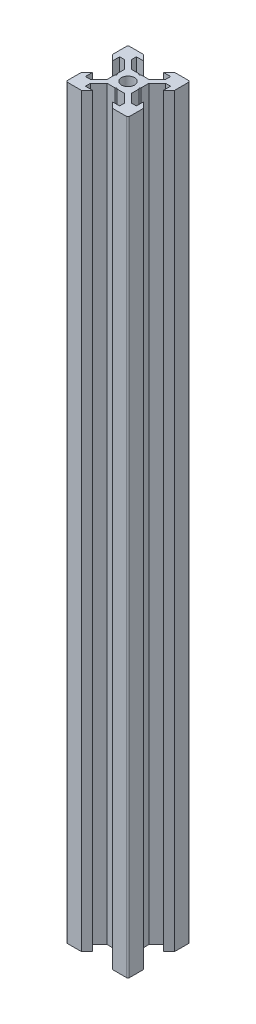
SolidWorks part; units mm, degrees
material "6063-O，挤压棒材(SS)"
ref_plane "前视基准面" through (0, 0, 0) normal (0, 0, 1) x (1, 0, 0)
ref_plane "上视基准面" through (0, 0, 0) normal (0, 1, 0) x (1, 0, 0)
ref_plane "右视基准面" through (0, 0, 0) normal (1, 0, 0) x (0, 0, -1)
other "Configuration Table"
sketch "草图1" plane through (0, 0, 0) normal (0, 1, 0) x (1, 0, 0)
  line L0 (-2.0109, 3.9) -> (2.0109, 3.9)
  line L1 (3.4251, 4.4858) -> (5.5, 6.5607)
  line L2 (5.5, 6.5607) -> (5.5, 8.2)
  line L3 (5.5, 8.2) -> (3.3, 8.2)
  line L4 (3.1, 8.4) -> (3.1, 9.3)
  line L5 (3.8, 10) -> (8.5, 10)
  line L6 (10, 8.5) -> (10, 3.8)
  line L7 (9.3, 3.1) -> (8.4, 3.1)
  line L8 (8.2, 3.3) -> (8.2, 5.5)
  line L9 (8.2, 5.5) -> (6.5607, 5.5)
  line L10 (6.5607, 5.5) -> (4.4858, 3.4251)
  line L11 (3.9, 2.0109) -> (3.9, -2.0109)
  line L12 (4.4858, -3.4251) -> (6.5607, -5.5)
  line L13 (6.5607, -5.5) -> (8.2, -5.5)
  line L14 (8.2, -5.5) -> (8.2, -3.3)
  line L15 (8.4, -3.1) -> (9.3, -3.1)
  line L16 (10, -3.8) -> (10, -8.5)
  line L17 (8.5, -10) -> (3.8, -10)
  line L18 (3.1, -9.3) -> (3.1, -8.4)
  line L19 (3.3, -8.2) -> (5.5, -8.2)
  line L20 (5.5, -8.2) -> (5.5, -6.5607)
  line L21 (5.5, -6.5607) -> (3.4251, -4.4858)
  line L22 (2.0109, -3.9) -> (-2.0109, -3.9)
  line L23 (-3.4251, -4.4858) -> (-5.5, -6.5607)
  line L24 (-5.5, -6.5607) -> (-5.5, -8.2)
  line L25 (-5.5, -8.2) -> (-3.3, -8.2)
  line L26 (-3.1, -8.4) -> (-3.1, -9.3)
  line L27 (-3.8, -10) -> (-8.5, -10)
  line L28 (-10, -8.5) -> (-10, -3.8)
  line L29 (-9.3, -3.1) -> (-8.4, -3.1)
  line L30 (-8.2, -3.3) -> (-8.2, -5.5)
  line L31 (-8.2, -5.5) -> (-6.5607, -5.5)
  line L32 (-6.5607, -5.5) -> (-4.4858, -3.4251)
  line L33 (-3.9, -2.0109) -> (-3.9, 2.0109)
  line L34 (-4.4858, 3.4251) -> (-6.5607, 5.5)
  line L35 (-6.5607, 5.5) -> (-8.2, 5.5)
  line L36 (-8.2, 5.5) -> (-8.2, 3.3)
  line L37 (-8.4, 3.1) -> (-9.3, 3.1)
  line L38 (-10, 3.8) -> (-10, 8.5)
  line L39 (-8.5, 10) -> (-3.8, 10)
  line L40 (-3.1, 9.3) -> (-3.1, 8.4)
  line L41 (-3.3, 8.2) -> (-5.5, 8.2)
  line L42 (-5.5, 8.2) -> (-5.5, 6.5607)
  line L43 (-5.5, 6.5607) -> (-3.4251, 4.4858)
  line L44 (-4.4858, 3.4251) -> (-3.4251, 4.4858) construction
  line L45 (3.4251, 4.4858) -> (4.4858, 3.4251) construction
  line L46 (4.4858, -3.4251) -> (3.4251, -4.4858) construction
  line L47 (-3.4251, -4.4858) -> (-4.4858, -3.4251) construction
  line L48 (3.9555, -3.9555) -> (-3.9555, 3.9555) construction
  line L49 (3.9555, 3.9555) -> (-3.9555, -3.9555) construction
  line L50 (-9.5, 3.3) -> (-9.5, 3.6)
  line L51 (-9.5, 3.6) -> (-9.8, 3.6)
  line L52 (-3.6, 9.8) -> (-3.6, 9.5)
  line L53 (-3.6, 9.5) -> (-3.3, 9.5)
  line L54 (3.3, 9.5) -> (3.6, 9.5)
  line L55 (3.6, 9.5) -> (3.6, 9.8)
  line L56 (9.5, 3.3) -> (9.5, 3.6)
  line L57 (9.5, 3.6) -> (9.8, 3.6)
  line L58 (9.5, -3.3) -> (9.5, -3.6)
  line L59 (9.5, -3.6) -> (9.8, -3.6)
  line L60 (3.3, -9.5) -> (3.6, -9.5)
  line L61 (3.6, -9.5) -> (3.6, -9.8)
  line L62 (-3.6, -9.8) -> (-3.6, -9.5)
  line L63 (-3.6, -9.5) -> (-3.3, -9.5)
  line L64 (-9.5, -3.3) -> (-9.5, -3.6)
  line L65 (-9.5, -3.6) -> (-9.8, -3.6)
  arc A1 (2.0109, 3.9) -> (3.4251, 4.4858) centre (2.0109, 5.9) ccw
  arc A2 (3.3, 8.2) -> (3.1, 8.4) centre (3.3, 8.4) cw
  arc A5 (8.5, 10) -> (10, 8.5) centre (8.5, 8.5) cw
  arc A8 (8.4, 3.1) -> (8.2, 3.3) centre (8.4, 3.3) cw
  arc A9 (4.4858, 3.4251) -> (3.9, 2.0109) centre (5.9, 2.0109) ccw
  arc A10 (3.9, -2.0109) -> (4.4858, -3.4251) centre (5.9, -2.0109) ccw
  arc A11 (8.2, -3.3) -> (8.4, -3.1) centre (8.4, -3.3) cw
  arc A14 (10, -8.5) -> (8.5, -10) centre (8.5, -8.5) cw
  arc A17 (3.1, -8.4) -> (3.3, -8.2) centre (3.3, -8.4) cw
  arc A18 (3.4251, -4.4858) -> (2.0109, -3.9) centre (2.0109, -5.9) ccw
  arc A19 (-2.0109, -3.9) -> (-3.4251, -4.4858) centre (-2.0109, -5.9) ccw
  arc A20 (-3.3, -8.2) -> (-3.1, -8.4) centre (-3.3, -8.4) cw
  arc A23 (-8.5, -10) -> (-10, -8.5) centre (-8.5, -8.5) cw
  arc A26 (-8.4, -3.1) -> (-8.2, -3.3) centre (-8.4, -3.3) cw
  arc A27 (-4.4858, -3.4251) -> (-3.9, -2.0109) centre (-5.9, -2.0109) ccw
  arc A28 (-3.9, 2.0109) -> (-4.4858, 3.4251) centre (-5.9, 2.0109) ccw
  arc A29 (-8.2, 3.3) -> (-8.4, 3.1) centre (-8.4, 3.3) cw
  arc A32 (-10, 8.5) -> (-8.5, 10) centre (-8.5, 8.5) cw
  arc A35 (-3.1, 8.4) -> (-3.3, 8.2) centre (-3.3, 8.4) cw
  arc A36 (-3.4251, 4.4858) -> (-2.0109, 3.9) centre (-2.0109, 5.9) ccw
  arc A37 (-9.3, 3.1) -> (-9.5, 3.3) centre (-9.3, 3.3) cw
  arc A39 (-3.8, 10) -> (-3.6, 9.8) centre (-3.8, 9.8) cw
  arc A40 (-3.3, 9.5) -> (-3.1, 9.3) centre (-3.3, 9.3) cw
  arc A41 (3.1, 9.3) -> (3.3, 9.5) centre (3.3, 9.3) cw
  arc A42 (3.6, 9.8) -> (3.8, 10) centre (3.8, 9.8) cw
  arc A43 (9.3, 3.1) -> (9.5, 3.3) centre (9.3, 3.3) ccw
  arc A44 (9.8, 3.6) -> (10, 3.8) centre (9.8, 3.8) ccw
  arc A45 (9.3, -3.1) -> (9.5, -3.3) centre (9.3, -3.3) cw
  arc A46 (9.8, -3.6) -> (10, -3.8) centre (9.8, -3.8) cw
  arc A47 (3.1, -9.3) -> (3.3, -9.5) centre (3.3, -9.3) ccw
  arc A48 (3.6, -9.8) -> (3.8, -10) centre (3.8, -9.8) ccw
  arc A49 (-3.8, -10) -> (-3.6, -9.8) centre (-3.8, -9.8) ccw
  arc A50 (-3.3, -9.5) -> (-3.1, -9.3) centre (-3.3, -9.3) ccw
  arc A51 (-9.3, -3.1) -> (-9.5, -3.3) centre (-9.3, -3.3) ccw
  arc A53 (-9.8, 3.6) -> (-10, 3.8) centre (-9.8, 3.8) cw
  arc A54 (-9.8, -3.6) -> (-10, -3.8) centre (-9.8, -3.8) ccw
  circle A55 centre (0, 0) radius 2.075
  point P119 (3.9, 0)
  dimension "D2" = 1.5
  dimension "D4" = 6.2
  dimension "D8" = 2
  dimension "D10" = 4.15
  dimension "D11" = 0.2
  dimension "D1" = 20
  dimension "D3" = 1.5
  dimension "D5" = 7.2
  dimension "D6" = 1.8
  dimension "D7" = 11
  dimension "D9" = 7.8
extrude "2020L" [suppressed] add sketch "草图1" along normal blind 240
hole_wizard "1-2020M5" [suppressed] positions "草图2" profile "草图3" tap size "M5" standard "GB"
sketch "草图2" [suppressed] plane through (0, 0, 0) normal (0, -1, 0) x (-1, 0, 0)
  point P0 (0, 0)
sketch "草图3" plane through (0, 0, 0) normal (1, 0, 0) x (0, 0, -1)
  line L0 (0, 0) -> (0, 13.6618)
  line L1 (0, 13.6618) -> (2.1, 12.4)
  line L2 (2.1, 12.4) -> (2.1, 0)
  line L5 (2.1, 0) -> (0, 0)
  line L10 (0, 13.6618) -> (-2.1, 12.4) construction
  line L11 (0, -6.35) -> (0, 107.95) construction
  dimension "螺纹孔钻头直径" = 4.2
  dimension "螺纹孔钻头深度" = 12.4
  dimension "导头角度" = 118
cosmetic thread "孔螺蚊线1" [suppressed] parameters "D1"=10, "D2"=5.2
hole_wizard "2-2020M5" [suppressed] positions "草图5" profile "草图6" tap size "M5" standard "GB"
sketch "草图5" [suppressed] plane through (0, 100, 0) normal (0, 1, 0) x (1, 0, 0)
  point P0 (0, 0)
sketch "草图6" plane through (0, 100, 0) normal (1, 0, 0) x (0, 0, 1)
  line L0 (0, 0) -> (0, 13.6618)
  line L1 (0, 13.6618) -> (2.1, 12.4)
  line L2 (2.1, 12.4) -> (2.1, 0)
  line L5 (2.1, 0) -> (0, 0)
  line L10 (0, 13.6618) -> (-2.1, 12.4) construction
  line L11 (0, -6.35) -> (0, 107.95) construction
  dimension "螺纹孔钻头直径" = 4.2
  dimension "螺纹孔钻头深度" = 12.4
  dimension "导头角度" = 118
cosmetic thread "孔螺蚊线2" [suppressed] parameters "D1"=10, "D2"=5
sketch "草图7" plane through (0, 0, 0) normal (0, 1, 0) x (1, 0, 0)
  line L88 (-10, 0) -> (10, 0) construction
  line L89 (-13.9555, 3.9555) -> (-6.0445, -3.9555) construction
  line L90 (-13.9555, -3.9555) -> (-6.0445, 3.9555) construction
  line L91 (6.0445, 3.9555) -> (13.9555, -3.9555) construction
  line L92 (6.0445, -3.9555) -> (13.9555, 3.9555) construction
  line L93 (-7.9891, 3.9) -> (-12.0109, 3.9)
  line L94 (-13.4251, 4.4858) -> (-15.5, 6.5607)
  line L95 (-15.5, 6.5607) -> (-15.5, 8.2)
  line L96 (-15.5, 8.2) -> (-13.1, 8.2)
  line L97 (-13.1, 8.2) -> (-13.1, 9.5)
  line L98 (-13.1, 9.5) -> (-13.6, 9.5)
  line L99 (-13.6, 9.5) -> (-13.6, 10)
  line L100 (-13.6, 10) -> (-18.5, 10)
  line L101 (-20, 8.5) -> (-20, 3.6)
  line L102 (-20, 3.6) -> (-19.5, 3.6)
  line L103 (-19.5, 3.6) -> (-19.5, 3.1)
  line L104 (-19.5, 3.1) -> (-18.2, 3.1)
  line L105 (-18.2, 3.1) -> (-18.2, 5.5)
  line L106 (-18.2, 5.5) -> (-16.5607, 5.5)
  line L107 (-16.5607, 5.5) -> (-14.4858, 3.4251)
  line L108 (-13.9, 2.0109) -> (-13.9, -2.0109)
  line L109 (-14.4858, -3.4251) -> (-16.5607, -5.5)
  line L110 (-16.5607, -5.5) -> (-18.2, -5.5)
  line L111 (-18.2, -5.5) -> (-18.2, -3.1)
  line L112 (-18.2, -3.1) -> (-19.5, -3.1)
  line L113 (-19.5, -3.1) -> (-19.5, -3.6)
  line L114 (-19.5, -3.6) -> (-20, -3.6)
  line L115 (-20, -3.6) -> (-20, -8.5)
  line L116 (-18.5, -10) -> (-13.6, -10)
  line L117 (-13.6, -10) -> (-13.6, -9.5)
  line L118 (-13.6, -9.5) -> (-13.1, -9.5)
  line L119 (-13.1, -9.5) -> (-13.1, -8.2)
  line L120 (-13.1, -8.2) -> (-15.5, -8.2)
  line L121 (-15.5, -8.2) -> (-15.5, -6.5607)
  line L122 (-15.5, -6.5607) -> (-13.4251, -4.4858)
  line L123 (-12.0109, -3.9) -> (-7.9891, -3.9)
  line L124 (-6.5749, -4.4858) -> (-4.5, -6.5607)
  line L125 (-4.5, -6.5607) -> (-4.5, -8.2)
  line L126 (-4.5, -8.2) -> (-6.9, -8.2)
  line L127 (-6.9, -8.2) -> (-6.9, -9.5)
  line L128 (-6.9, -9.5) -> (-6.4, -9.5)
  line L129 (-6.4, -9.5) -> (-6.4, -10)
  line L130 (-6.4, -10) -> (6.4, -10)
  line L131 (6.4, -10) -> (6.4, -9.5)
  line L132 (6.4, -9.5) -> (6.9, -9.5)
  line L133 (6.9, -9.5) -> (6.9, -8.2)
  line L134 (6.9, -8.2) -> (4.5, -8.2)
  line L135 (4.5, -8.2) -> (4.5, -6.5607)
  line L136 (4.5, -6.5607) -> (6.5749, -4.4858)
  line L137 (7.9891, -3.9) -> (12.0109, -3.9)
  line L138 (13.4251, -4.4858) -> (15.5, -6.5607)
  line L139 (15.5, -6.5607) -> (15.5, -8.2)
  line L140 (15.5, -8.2) -> (13.1, -8.2)
  line L141 (13.1, -8.2) -> (13.1, -9.5)
  line L142 (13.1, -9.5) -> (13.6, -9.5)
  line L143 (13.6, -9.5) -> (13.6, -10)
  line L144 (13.6, -10) -> (18.5, -10)
  line L145 (20, -8.5) -> (20, -3.6)
  line L146 (20, -3.6) -> (19.5, -3.6)
  line L147 (19.5, -3.6) -> (19.5, -3.1)
  line L148 (19.5, -3.1) -> (18.2, -3.1)
  line L149 (18.2, -3.1) -> (18.2, -5.5)
  line L150 (18.2, -5.5) -> (16.5607, -5.5)
  line L151 (16.5607, -5.5) -> (14.4858, -3.4251)
  line L152 (13.9, -2.0109) -> (13.9, 2.0109)
  line L153 (14.4858, 3.4251) -> (16.5607, 5.5)
  line L154 (16.5607, 5.5) -> (18.2, 5.5)
  line L155 (18.2, 5.5) -> (18.2, 3.1)
  line L156 (18.2, 3.1) -> (19.5, 3.1)
  line L157 (19.5, 3.1) -> (19.5, 3.6)
  line L158 (19.5, 3.6) -> (20, 3.6)
  line L159 (20, 3.6) -> (20, 8.5)
  line L160 (18.5, 10) -> (13.6, 10)
  line L161 (13.6, 10) -> (13.6, 9.5)
  line L162 (13.6, 9.5) -> (13.1, 9.5)
  line L163 (13.1, 9.5) -> (13.1, 8.2)
  line L164 (13.1, 8.2) -> (15.5, 8.2)
  line L165 (15.5, 8.2) -> (15.5, 6.5607)
  line L166 (15.5, 6.5607) -> (13.4251, 4.4858)
  line L167 (12.0109, 3.9) -> (7.9891, 3.9)
  line L168 (6.5749, 4.4858) -> (4.5, 6.5607)
  line L169 (4.5, 6.5607) -> (4.5, 8.2)
  line L170 (4.5, 8.2) -> (6.9, 8.2)
  line L171 (6.9, 8.2) -> (6.9, 9.5)
  line L172 (6.9, 9.5) -> (6.4, 9.5)
  line L173 (6.4, 9.5) -> (6.4, 10)
  line L174 (6.4, 10) -> (-6.4, 10)
  line L175 (-6.4, 10) -> (-6.4, 9.5)
  line L176 (-6.4, 9.5) -> (-6.9, 9.5)
  line L177 (-6.9, 9.5) -> (-6.9, 8.2)
  line L178 (-6.9, 8.2) -> (-4.5, 8.2)
  line L179 (-4.5, 8.2) -> (-4.5, 6.5607)
  line L180 (-4.5, 6.5607) -> (-6.5749, 4.4858)
  line L181 (-14.4858, 3.4251) -> (-13.4251, 4.4858) construction
  line L182 (-14.4858, -3.4251) -> (-13.4251, -4.4858) construction
  line L183 (13.4251, -4.4858) -> (14.4858, -3.4251) construction
  line L184 (13.4251, 4.4858) -> (14.4858, 3.4251) construction
  line L185 (-2.3787, 8.2) -> (2.3787, 8.2)
  line L186 (2.3787, 8.2) -> (2.3787, 6.5607)
  line L187 (2.3787, 6.5607) -> (5.5142, 3.4251)
  line L188 (6.1, 2.0109) -> (6.1, -2.0109)
  line L189 (5.5142, -3.4251) -> (2.3787, -6.5607)
  line L190 (2.3787, -6.5607) -> (2.3787, -8.2)
  line L191 (2.3787, -8.2) -> (-2.3787, -8.2)
  line L192 (-2.3787, -8.2) -> (-2.3787, -6.5607)
  line L193 (-2.3787, -6.5607) -> (-5.5142, -3.4251)
  line L194 (-6.1, -2.0109) -> (-6.1, 2.0109)
  line L195 (-5.5142, 3.4251) -> (-2.3787, 6.5607)
  line L196 (-2.3787, 6.5607) -> (-2.3787, 8.2)
  line L197 (-6.5749, 4.4858) -> (-5.5142, 3.4251) construction
  line L198 (-6.5749, -4.4858) -> (-5.5142, -3.4251) construction
  line L199 (5.5142, 3.4251) -> (6.5749, 4.4858) construction
  line L200 (5.5142, -3.4251) -> (6.5749, -4.4858) construction
  arc A16 (-12.0109, 3.9) -> (-13.4251, 4.4858) centre (-12.0109, 5.9) cw
  arc A17 (-18.5, 10) -> (-20, 8.5) centre (-18.5, 8.5) ccw
  arc A18 (-14.4858, 3.4251) -> (-13.9, 2.0109) centre (-15.9, 2.0109) cw
  arc A19 (-13.9, -2.0109) -> (-14.4858, -3.4251) centre (-15.9, -2.0109) cw
  arc A20 (-20, -8.5) -> (-18.5, -10) centre (-18.5, -8.5) ccw
  arc A21 (-13.4251, -4.4858) -> (-12.0109, -3.9) centre (-12.0109, -5.9) cw
  arc A22 (-7.9891, -3.9) -> (-6.5749, -4.4858) centre (-7.9891, -5.9) cw
  arc A23 (6.5749, -4.4858) -> (7.9891, -3.9) centre (7.9891, -5.9) cw
  arc A24 (12.0109, -3.9) -> (13.4251, -4.4858) centre (12.0109, -5.9) cw
  arc A25 (18.5, -10) -> (20, -8.5) centre (18.5, -8.5) ccw
  arc A26 (14.4858, -3.4251) -> (13.9, -2.0109) centre (15.9, -2.0109) cw
  arc A27 (13.9, 2.0109) -> (14.4858, 3.4251) centre (15.9, 2.0109) cw
  arc A28 (20, 8.5) -> (18.5, 10) centre (18.5, 8.5) ccw
  arc A29 (13.4251, 4.4858) -> (12.0109, 3.9) centre (12.0109, 5.9) cw
  arc A30 (7.9891, 3.9) -> (6.5749, 4.4858) centre (7.9891, 5.9) cw
  arc A31 (-6.5749, 4.4858) -> (-7.9891, 3.9) centre (-7.9891, 5.9) cw
  arc A32 (5.5142, 3.4251) -> (6.1, 2.0109) centre (4.1, 2.0109) cw
  arc A33 (6.1, -2.0109) -> (5.5142, -3.4251) centre (4.1, -2.0109) cw
  arc A34 (-5.5142, -3.4251) -> (-6.1, -2.0109) centre (-4.1, -2.0109) cw
  arc A35 (-6.1, 2.0109) -> (-5.5142, 3.4251) centre (-4.1, 2.0109) cw
  circle A36 centre (-10, 0) radius 2.075
  circle A37 centre (10, 0) radius 2.075
  point P177 (0, 10)
  point P178 (0, -10)
  dimension "D5" = 2
  dimension "D8" = 1.5
  dimension "D13" = 4.15
  dimension "D1" = 20
  dimension "D2" = 45
  dimension "D3" = 45
  dimension "D4" = 7.8
  dimension "D6" = 1.5
  dimension "D7" = 40
  dimension "D9" = 6.2
  dimension "D10" = 7.2
  dimension "D11" = 1.8
  dimension "D12" = 11
extrude "2040L" [suppressed] add sketch "草图7" along normal blind 240
fillet "圆角1" [suppressed] radius 0.25
sketch "草图8" [suppressed] plane through (0, 0, 0) normal (0, -1, 0) x (1, 0, 0)
  circle A0 centre (10, 0) radius 2.075 construction
  circle A1 centre (-10, 0) radius 2.075 construction
  point P0 (-10, 0)
  point P1 (10, 0)
hole_wizard "1-2040M5" [suppressed] positions "草图13" profile "草图14" tap size "M5" standard "GB"
sketch "草图13" [suppressed] plane through (0, 0, 0) normal (0, -1, 0) x (-1, 0, 0)
  point P0 (-10, 0)
sketch "草图14" plane through (10, 0, 0) normal (1, 0, 0) x (0, 0, -1)
  line L0 (0, 0) -> (0, 13.6618)
  line L1 (0, 13.6618) -> (2.1, 12.4)
  line L2 (2.1, 12.4) -> (2.1, 0)
  line L5 (2.1, 0) -> (0, 0)
  line L10 (0, 13.6618) -> (-2.1, 12.4) construction
  line L11 (0, -6.35) -> (0, 107.95) construction
  dimension "螺纹孔钻头直径" = 4.2
  dimension "螺纹孔钻头深度" = 12.4
  dimension "导头角度" = 118
cosmetic thread "孔螺蚊线7" [suppressed] parameters "D1"=10, "D2"=5
hole_wizard "2-2040M5" [suppressed] positions "草图15" profile "草图16" tap size "M5" standard "GB"
sketch "草图15" [suppressed] plane through (0, 0, 0) normal (0, -1, 0) x (-1, 0, 0)
  point P0 (10, 0)
sketch "草图16" plane through (-10, 0, 0) normal (1, 0, 0) x (0, 0, -1)
  line L0 (0, 0) -> (0, 13.6618)
  line L1 (0, 13.6618) -> (2.1, 12.4)
  line L2 (2.1, 12.4) -> (2.1, 0)
  line L5 (2.1, 0) -> (0, 0)
  line L10 (0, 13.6618) -> (-2.1, 12.4) construction
  line L11 (0, -6.35) -> (0, 107.95) construction
  dimension "螺纹孔钻头直径" = 4.2
  dimension "螺纹孔钻头深度" = 12.4
  dimension "导头角度" = 118
cosmetic thread "孔螺蚊线8" [suppressed] parameters "D1"=10, "D2"=5
hole_wizard "3-2040M5" [suppressed] positions "草图19" profile "草图20" tap size "M5" standard "GB"
sketch "草图19" [suppressed] plane through (0, 100, 0) normal (0, 1, 0) x (1, 0, 0)
  point P0 (10, 0)
sketch "草图20" plane through (10, 100, 0) normal (1, 0, 0) x (0, 0, 1)
  line L0 (0, 0) -> (0, 13.6618)
  line L1 (0, 13.6618) -> (2.1, 12.4)
  line L2 (2.1, 12.4) -> (2.1, 0)
  line L5 (2.1, 0) -> (0, 0)
  line L10 (0, 13.6618) -> (-2.1, 12.4) construction
  line L11 (0, -6.35) -> (0, 107.95) construction
  dimension "螺纹孔钻头直径" = 4.2
  dimension "螺纹孔钻头深度" = 12.4
  dimension "导头角度" = 118
cosmetic thread "孔螺蚊线10" [suppressed] parameters "D1"=10, "D2"=5
hole_wizard "4-2040M5" [suppressed] positions "草图21" profile "草图22" tap size "M5" standard "GB"
sketch "草图21" [suppressed] plane through (0, 100, 0) normal (0, 1, 0) x (1, 0, 0)
  point P0 (-10, 0)
sketch "草图22" plane through (-10, 100, 0) normal (1, 0, 0) x (0, 0, 1)
  line L0 (0, 0) -> (0, 13.6618)
  line L1 (0, 13.6618) -> (2.1, 12.4)
  line L2 (2.1, 12.4) -> (2.1, 0)
  line L5 (2.1, 0) -> (0, 0)
  line L10 (0, 13.6618) -> (-2.1, 12.4) construction
  line L11 (0, -6.35) -> (0, 107.95) construction
  dimension "螺纹孔钻头直径" = 4.2
  dimension "螺纹孔钻头深度" = 12.4
  dimension "导头角度" = 118
cosmetic thread "孔螺蚊线11" [suppressed] parameters "D1"=10, "D2"=5
sketch "草图23" plane through (0, 0, 0) normal (0, 1, 0) x (1, 0, 0)
  line L0 (-3.9, 2.0109) -> (-3.9, -2.0109)
  line L1 (-4.4858, -3.4251) -> (-6.5607, -5.5)
  line L2 (-6.5607, -5.5) -> (-8.2, -5.5)
  line L3 (-8.2, -5.5) -> (-8.2, -3.1)
  line L4 (-8.2, -3.1) -> (-9.5, -3.1)
  line L5 (-9.5, -3.1) -> (-9.5, -3.6)
  line L6 (-9.5, -3.6) -> (-10, -3.6)
  line L7 (-10, -3.6) -> (-10, -8.5)
  line L8 (-8.5, -10) -> (-3.6, -10)
  line L9 (-3.6, -10) -> (-3.6, -9.5)
  line L10 (-3.6, -9.5) -> (-3.1, -9.5)
  line L11 (-3.1, -9.5) -> (-3.1, -8.2)
  line L12 (-3.1, -8.2) -> (-5.5, -8.2)
  line L13 (-5.5, -8.2) -> (-5.5, -6.5607)
  line L14 (-5.5, -6.5607) -> (-3.4251, -4.4858)
  line L15 (-2.0109, -3.9) -> (2.0109, -3.9)
  line L16 (3.4251, -4.4858) -> (5.5, -6.5607)
  line L17 (5.5, -6.5607) -> (5.5, -8.2)
  line L18 (5.5, -8.2) -> (3.1, -8.2)
  line L19 (3.1, -8.2) -> (3.1, -9.5)
  line L20 (3.1, -9.5) -> (3.6, -9.5)
  line L21 (3.6, -9.5) -> (3.6, -10)
  line L22 (3.6, -10) -> (8.5, -10)
  line L23 (-10, 8.5) -> (-10, 3.6)
  line L24 (-10, 3.6) -> (-9.5, 3.6)
  line L25 (-9.5, 3.6) -> (-9.5, 3.1)
  line L26 (-9.5, 3.1) -> (-8.2, 3.1)
  line L27 (-8.2, 3.1) -> (-8.2, 5.5)
  line L28 (-8.2, 5.5) -> (-6.5607, 5.5)
  line L29 (-6.5607, 5.5) -> (-4.4858, 3.4251)
  line L30 (-3.9555, -3.9555) -> (3.9555, 3.9555) construction
  line L31 (-3.9555, 3.9555) -> (3.9555, -3.9555) construction
  line L32 (-4.4858, -3.4251) -> (-3.4251, -4.4858) construction
  line L39 (-4.4858, 3.4251) -> (-3.4251, 4.4858) construction
  line L40 (3.4251, -4.4858) -> (4.4858, -3.4251) construction
  line L41 (-3.4251, 4.4858) -> (-5.5, 6.5607)
  line L42 (-5.5, 6.5607) -> (-5.5, 8.2332)
  line L43 (2.6122, 3.9) -> (-2.0109, 3.9)
  line L44 (3.9, 2.6122) -> (3.9, -2.0109)
  line L45 (6.5607, -5.5) -> (8.2332, -5.5)
  line L46 (4.4858, -3.4251) -> (6.5607, -5.5)
  arc A0 (-3.9, -2.0109) -> (-4.4858, -3.4251) centre (-5.9, -2.0109) cw
  arc A1 (-10, -8.5) -> (-8.5, -10) centre (-8.5, -8.5) ccw
  arc A2 (-3.4251, -4.4858) -> (-2.0109, -3.9) centre (-2.0109, -5.9) cw
  arc A3 (2.0109, -3.9) -> (3.4251, -4.4858) centre (2.0109, -5.9) cw
  arc A4 (8.5, -10) -> (10, -8.5) centre (8.5, -8.5) ccw
  arc A5 (10, -8.5) -> (-8.5, 10) centre (-8.5, -8.5) ccw
  arc A6 (-8.5, 10) -> (-10, 8.5) centre (-8.5, 8.5) ccw
  arc A7 (-4.4858, 3.4251) -> (-3.9, 2.0109) centre (-5.9, 2.0109) cw
  arc A14 (-5.5, 8.2332) -> (2.7444, 4.25) centre (-8.5, -8.5) cw
  arc A15 (2.7444, 4.25) -> (2.6122, 3.9) centre (2.6122, 4.1) cw
  arc A16 (-2.0109, 3.9) -> (-3.4251, 4.4858) centre (-2.0109, 5.9) cw
  arc A17 (4.25, 2.7444) -> (3.9, 2.6122) centre (4.1, 2.6122) ccw
  arc A18 (8.2332, -5.5) -> (4.25, 2.7444) centre (-8.5, -8.5) ccw
  arc A19 (3.9, -2.0109) -> (4.4858, -3.4251) centre (5.9, -2.0109) ccw
  circle A20 centre (0, 0) radius 2.075
  dimension "D3" = 1.5
  dimension "D5" = 2
  dimension "D10" = 17
  dimension "D11" = 0.2
  dimension "D12" = 4.15
  dimension "D1" = 20
  dimension "D2" = 1.5
  dimension "D4" = 11
  dimension "D6" = 1.8
  dimension "D7" = 3.9
  dimension "D8" = 6.2
  dimension "D9" = 7.2
extrude "2020R" [suppressed] add sketch "草图23" along normal blind 240
fillet "圆角2" [suppressed] radius 0.25
hole_wizard "1-2020R" [suppressed] positions "草图24" profile "草图25" tap size "M5" standard "GB"
sketch "草图24" [suppressed] plane through (0, 100, 0) normal (0, 1, 0) x (1, 0, 0)
  point P0 (0, 0)
sketch "草图25" plane through (0, 100, 0) normal (1, 0, 0) x (0, 0, 1)
  line L0 (0, 0) -> (0, 13.6618)
  line L1 (0, 13.6618) -> (2.1, 12.4)
  line L2 (2.1, 12.4) -> (2.1, 0)
  line L5 (2.1, 0) -> (0, 0)
  line L10 (0, 13.6618) -> (-2.1, 12.4) construction
  line L11 (0, -6.35) -> (0, 107.95) construction
  dimension "螺纹孔钻头直径" = 4.2
  dimension "螺纹孔钻头深度" = 12.4
  dimension "导头角度" = 118
cosmetic thread "孔螺蚊线12" parameters "D1"=10, "D2"=5
hole_wizard "2-2020R" [suppressed] positions "草图26" profile "草图27" tap size "M5" standard "GB"
sketch "草图26" [suppressed] plane through (0, 0, 0) normal (0, -1, 0) x (-1, 0, 0)
  point P0 (0, 0)
sketch "草图27" plane through (0, 0, 0) normal (1, 0, 0) x (0, 0, -1)
  line L0 (0, 0) -> (0, 13.6618)
  line L1 (0, 13.6618) -> (2.1, 12.4)
  line L2 (2.1, 12.4) -> (2.1, 0)
  line L5 (2.1, 0) -> (0, 0)
  line L10 (0, 13.6618) -> (-2.1, 12.4) construction
  line L11 (0, -6.35) -> (0, 107.95) construction
  dimension "螺纹孔钻头直径" = 4.2
  dimension "螺纹孔钻头深度" = 12.4
  dimension "导头角度" = 118
cosmetic thread "孔螺蚊线13" parameters "D1"=10, "D2"=5
sketch "草图28" plane through (0, 0, 0) normal (0, 1, 0) x (1, 0, 0)
  line L56 (-3.9, 2.8393) -> (-3.9, 0.2828)
  line L57 (-3.9, 0.2828) -> (-3.6172, 0)
  line L58 (-3.6172, 0) -> (-3.9, -0.2828)
  line L59 (-3.9, -0.2828) -> (-3.9, -2.8393)
  line L60 (-3.9, -2.8393) -> (-6.5607, -5.5)
  line L61 (-6.5607, -5.5) -> (-8.2, -5.5)
  line L62 (-8.2, -5.5) -> (-8.2, -3.15)
  line L63 (-8.2, -3.15) -> (-10, -4.95)
  line L64 (-10, -4.95) -> (-10, -9.5)
  line L65 (-9.5, -10) -> (-4.95, -10)
  line L66 (-4.95, -10) -> (-3.15, -8.2)
  line L67 (-3.15, -8.2) -> (-5.5, -8.2)
  line L68 (-5.5, -8.2) -> (-5.5, -6.5607)
  line L69 (-5.5, -6.5607) -> (-2.8393, -3.9)
  line L70 (-2.8393, -3.9) -> (-0.2828, -3.9)
  line L71 (-0.2828, -3.9) -> (0, -3.6172)
  line L72 (0, -3.6172) -> (0.2828, -3.9)
  line L73 (0.2828, -3.9) -> (2.8393, -3.9)
  line L74 (2.8393, -3.9) -> (5.5, -6.5607)
  line L75 (5.5, -6.5607) -> (5.5, -8.2)
  line L76 (5.5, -8.2) -> (3.15, -8.2)
  line L77 (3.15, -8.2) -> (4.95, -10)
  line L78 (4.95, -10) -> (9.5, -10)
  line L79 (10, -9.5) -> (10, -4.95)
  line L80 (10, -4.95) -> (8.2, -3.15)
  line L81 (8.2, -3.15) -> (8.2, -5.5)
  line L82 (8.2, -5.5) -> (6.5607, -5.5)
  line L83 (6.5607, -5.5) -> (3.9, -2.8393)
  line L84 (3.9, -2.8393) -> (3.9, -0.2828)
  line L85 (3.9, -0.2828) -> (3.6172, 0)
  line L86 (3.6172, 0) -> (3.9, 0.2828)
  line L87 (3.9, 0.2828) -> (3.9, 2.8393)
  line L88 (3.9, 2.8393) -> (6.5607, 5.5)
  line L89 (6.5607, 5.5) -> (8.2, 5.5)
  line L90 (8.2, 5.5) -> (8.2, 3.15)
  line L91 (8.2, 3.15) -> (10, 4.95)
  line L92 (10, 4.95) -> (10, 9.5)
  line L93 (9.5, 10) -> (4.95, 10)
  line L94 (4.95, 10) -> (3.15, 8.2)
  line L95 (3.15, 8.2) -> (5.5, 8.2)
  line L96 (5.5, 8.2) -> (5.5, 6.5607)
  line L97 (5.5, 6.5607) -> (2.8393, 3.9)
  line L98 (2.8393, 3.9) -> (0.2828, 3.9)
  line L99 (0.2828, 3.9) -> (0, 3.6172)
  line L100 (0, 3.6172) -> (-0.2828, 3.9)
  line L101 (-0.2828, 3.9) -> (-2.8393, 3.9)
  line L102 (-2.8393, 3.9) -> (-5.5, 6.5607)
  line L103 (-5.5, 6.5607) -> (-5.5, 8.2)
  line L104 (-5.5, 8.2) -> (-3.15, 8.2)
  line L105 (-3.15, 8.2) -> (-4.95, 10)
  line L106 (-4.95, 10) -> (-9.5, 10)
  line L107 (-10, 9.5) -> (-10, 4.95)
  line L108 (-10, 4.95) -> (-8.2, 3.15)
  line L109 (-8.2, 3.15) -> (-8.2, 5.5)
  line L110 (-8.2, 5.5) -> (-6.5607, 5.5)
  line L111 (-6.5607, 5.5) -> (-3.9, 2.8393)
  line L112 (-2.8393, 3.9) -> (-3.9, 2.8393) construction
  line L113 (-3.9, -2.8393) -> (-2.8393, -3.9) construction
  line L114 (2.8393, -3.9) -> (3.9, -2.8393) construction
  line L115 (2.8393, 3.9) -> (3.9, 2.8393) construction
  line L116 (-3.3697, 3.3697) -> (3.3697, -3.3697) construction
  line L117 (-3.3697, -3.3697) -> (3.3697, 3.3697) construction
  arc A4 (-10, -9.5) -> (-9.5, -10) centre (-9.5, -9.5) ccw
  arc A5 (9.5, -10) -> (10, -9.5) centre (9.5, -9.5) ccw
  arc A6 (10, 9.5) -> (9.5, 10) centre (9.5, 9.5) ccw
  arc A7 (-9.5, 10) -> (-10, 9.5) centre (-9.5, 9.5) ccw
  circle A8 centre (0, 0) radius 2.075
  dimension "D7" = 0.5
  dimension "D9" = 4.15
  dimension "D1" = 7.8
  dimension "D2" = 20
  dimension "D3" = 1.5
  dimension "D4" = 0.4
  dimension "D5" = 11
  dimension "D6" = 6.3
  dimension "D8" = 1.8
extrude "2020V" add sketch "草图28" along normal blind 240
hole_wizard "1-2020V" positions "草图29" profile "草图30" tap size "M5" standard "GB"
sketch "草图29" plane through (0, 240, 0) normal (0, 1, 0) x (1, 0, 0)
  point P0 (0, 0)
sketch "草图30" plane through (0, 240, 0) normal (1, 0, 0) x (0, 0, 1)
  line L0 (0, 0) -> (0, 13.6618)
  line L1 (0, 13.6618) -> (2.1, 12.4)
  line L2 (2.1, 12.4) -> (2.1, 0)
  line L5 (2.1, 0) -> (0, 0)
  line L10 (0, 13.6618) -> (-2.1, 12.4) construction
  line L11 (0, -6.35) -> (0, 107.95) construction
  dimension "螺纹孔钻头直径" = 4.2
  dimension "螺纹孔钻头深度" = 12.4
  dimension "导头角度" = 118
cosmetic thread "孔螺蚊线14" parameters "D1"=10, "D2"=5
hole_wizard "2-2020V" positions "草图31" profile "草图32" tap size "M5" standard "GB"
sketch "草图31" plane through (0, 0, 0) normal (0, -1, 0) x (-1, 0, 0)
  point P0 (0, 0)
sketch "草图32" plane through (0, 0, 0) normal (1, 0, 0) x (0, 0, -1)
  line L0 (0, 0) -> (0, 13.6618)
  line L1 (0, 13.6618) -> (2.1, 12.4)
  line L2 (2.1, 12.4) -> (2.1, 0)
  line L5 (2.1, 0) -> (0, 0)
  line L10 (0, 13.6618) -> (-2.1, 12.4) construction
  line L11 (0, -6.35) -> (0, 107.95) construction
  dimension "螺纹孔钻头直径" = 4.2
  dimension "螺纹孔钻头深度" = 12.4
  dimension "导头角度" = 118
cosmetic thread "孔螺蚊线15" parameters "D1"=10, "D2"=5
equation "\"L\" = 240'型材长度"
equation "\"L@2020L\" = \"L\""
equation "\"L@2040L\"= \"L\""
equation "\"L@2020R\"= \"L\""
equation "\"L@2020V\"= \"L\""
